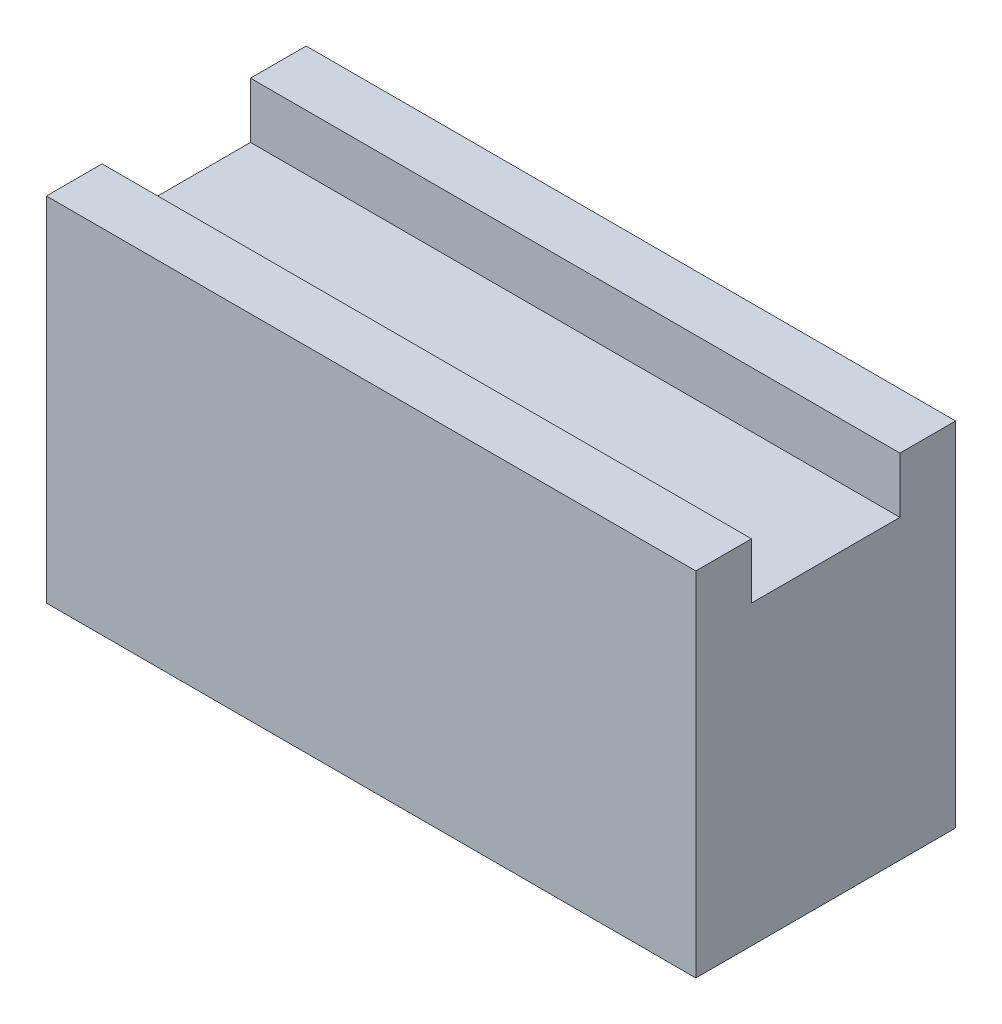
SolidWorks part; units mm, degrees
ref_plane "Front Plane" through (0, 0, 0) normal (0, 0, 1) x (1, 0, 0)
ref_plane "Top Plane" through (0, 0, 0) normal (0, 1, 0) x (1, 0, 0)
ref_plane "Right Plane" through (0, 0, 0) normal (1, 0, 0) x (0, 0, -1)
sketch "Sketch1" plane through (0, 0, 0) normal (1, 0, 0) x (0, 0, -1)
  line L0 (-7, 8) -> (-7, 11)
  line L1 (-7, -8) -> (7, -8)
  line L2 (-7, -8) -> (-7, 8)
  line L3 (-4, 8) -> (4, 8)
  line L4 (7, -8) -> (7, 8)
  line L5 (-7, -8) -> (7, 8) construction
  line L6 (-7, 8) -> (7, -8) construction
  line L7 (-7, 11) -> (-4, 11)
  line L8 (-4, 11) -> (-4, 8)
  line L9 (7, 8) -> (7, 11)
  line L10 (7, 11) -> (4, 11)
  line L11 (4, 11) -> (4, 8)
  point P0 (0, 0)
  point P12 (0, 8)
  dimension "D1" = 16
  dimension "D2" = 8
  dimension "D3" = 3
  dimension "D4" = 3
extrude "Boss-Extrude1" add sketch "Sketch1" against normal blind 35
